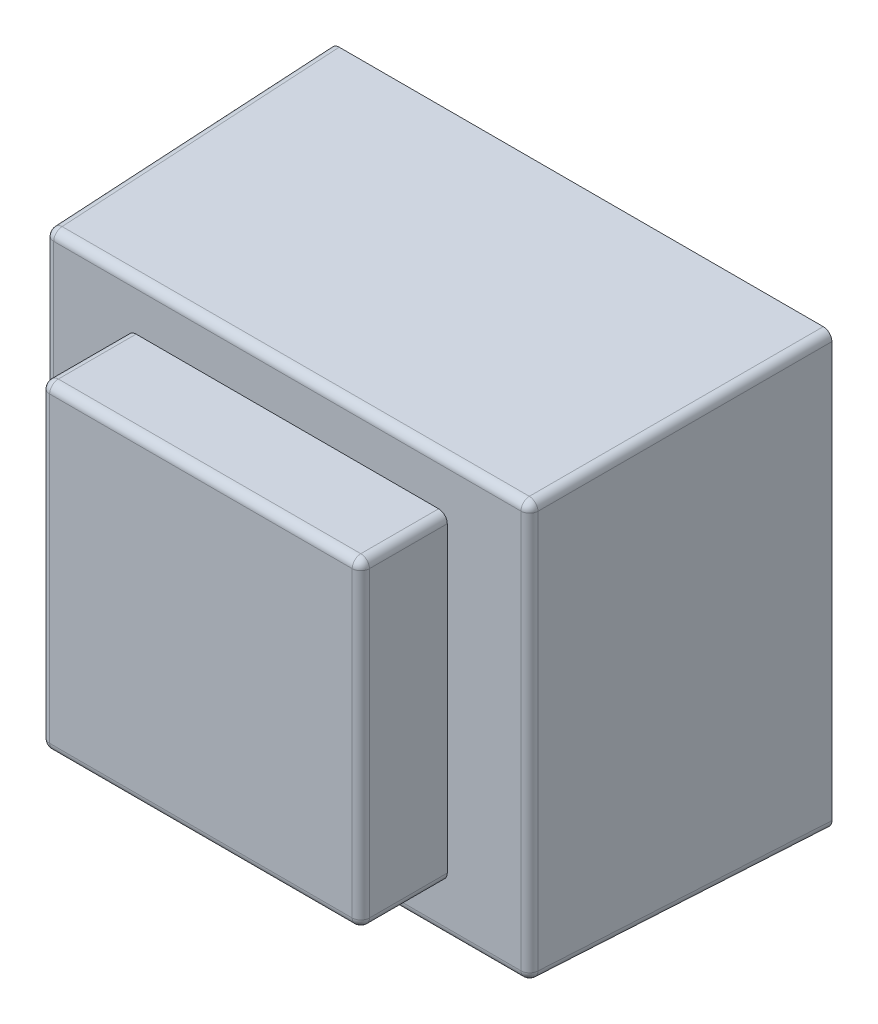
SolidWorks part; units mm, degrees
material "Медь"
ref_plane "Спереди (Плоскость XY)" through (0, 0, 0) normal (0, 0, 1) x (1, 0, 0)
ref_plane "Сверху (Плоскость XZ)" through (0, 0, 0) normal (0, 1, 0) x (1, 0, 0)
ref_plane "Справа (Плоскость ZY)" through (0, 0, 0) normal (1, 0, 0) x (0, 0, -1)
sketch "Эскиз1" plane through (0, 0, 0) normal (0, 1, 0) x (1, 0, 0)
  line L0 (0, 0) -> (58, 0) construction
  line L1 (-29, 0) -> (-28, -34)
  line L2 (-28, -34) -> (28, -34)
  line L3 (28, -34) -> (29, 0)
  line L4 (29, 0) -> (-29, 0)
  line L5 (0, 0) -> (0, -34) construction
  point P9 (0, 0)
  point P12 (81.2325, -36.5426)
  dimension "D1" = 58
  dimension "D2" = 56
  dimension "D3" = 34
  dimension "D4" = 58
extrude "Бобышка-Вытянуть3" add sketch "Эскиз1" along normal mid plane 50
sketch "Эскиз3" plane through (0, 0, 0) normal (1, 0, 0) x (0, 0, -1)
  line L2 (-34, 25) -> (-34, -25) construction
  line L3 (0, 25) -> (-34, 24)
  line L4 (0, -25) -> (-34, -24)
  line L8 (0, -25) -> (0, 25)
  line L10 (-34, 24) -> (-34, -24)
  line L11 (-34, 0) -> (0, 0) construction
  dimension "D1" = 48
extrude "Вырез-Вытянуть1" cut sketch "Эскиз3" along normal through all both and the other way through all flip side to cut
sketch "Эскиз4" plane through (0, 0, 34) normal (0, 0, 1) x (1, 0, 0)
  line L1 (-18.5, -18.5) -> (18.5, -18.5)
  line L2 (-18.5, -18.5) -> (-18.5, 18.5)
  line L3 (-18.5, 18.5) -> (18.5, 18.5)
  line L4 (18.5, -18.5) -> (18.5, 18.5)
  line L5 (-18.5, -18.5) -> (18.5, 18.5) construction
  line L6 (-18.5, 18.5) -> (18.5, -18.5) construction
  point P0 (0, 0)
  point P5 (0, 0)
  dimension "D1" = 37
extrude "Бобышка-Вытянуть4" add sketch "Эскиз4" along normal blind 10
sketch "Эскиз8" plane through (0, 0, 0) normal (0, 0, -1) x (1, 0, 0)
  line L0 (-22, 0) -> (22, 0) construction
  line L1 (20.6, 1.4) -> (23.4, 1.4)
  line L2 (20.6, 1.4) -> (20.6, -1.4)
  line L3 (20.6, -1.4) -> (23.4, -1.4)
  line L4 (23.4, 1.4) -> (23.4, -1.4)
  line L5 (20.6, 1.4) -> (23.4, -1.4) construction
  line L6 (20.6, -1.4) -> (23.4, 1.4) construction
  line L7 (-23.4, 1.4) -> (-20.6, 1.4)
  line L8 (-23.4, 1.4) -> (-23.4, -1.4)
  line L9 (-23.4, -1.4) -> (-20.6, -1.4)
  line L10 (-20.6, 1.4) -> (-20.6, -1.4)
  line L11 (-23.4, 1.4) -> (-20.6, -1.4) construction
  line L12 (-23.4, -1.4) -> (-20.6, 1.4) construction
  point P0 (22, 0)
  point P5 (-22, 0)
  point P12 (0, 0)
  point P13 (0, 0)
  dimension "D1" = 2.8
  dimension "D2" = 44
extrude "Вырез-Вытянуть3" cut sketch "Эскиз8" against normal blind 10
sketch "Эскиз5" plane through (0, 0, 0) normal (0, 0, -1) x (1, 0, 0)
  line L4 (27.5, 23.5) -> (-27.5, 23.5)
  line L5 (27.5, 23.5) -> (-27.5, 23.5)
  line L6 (-27.5, -23.5) -> (27.5, -23.5)
  line L12 (-27.5, -23.5) -> (27.5, -23.5)
  line L13 (27.5, -23.5) -> (27.5, 23.5)
  line L15 (-27.5, 23.5) -> (-27.5, -23.5)
  line L17 (27.5, -23.5) -> (27.5, 23.5)
  line L19 (-27.5, 23.5) -> (-27.5, -23.5)
  dimension "D1" = 1.5
extrude "Вырез-Вытянуть2" cut sketch "Эскиз5" against normal blind 0.7
fillet "Скругление1" radius 1 16 edges at (0, -18.5, 44) (-18.5, 0, 44) (0, 18.5, 44) (18.5, 0, 44) (-18.5, 18.5, 39) (-18.5, -18.5, 39) (18.5, -18.5, 39) (18.5, 18.5, 39) (28, 0, 34) (-28, 0, 34) (-28.5, 24.5, 17) (-28.5, -24.5, 17) (0, -24, 34) (28.5, -24.5, 17) (28.5, 24.5, 17) (0, 24, 34)
sketch "Эскиз7" plane through (0, -0.7, 0.7) normal (0, 0, -1) x (1, 0, 0)
  line L0 (0, 0) -> (56.4992, 0) construction
  line L1 (5, 15.8) -> (-5, 15.8) construction
  line L3 (0, -17.2) -> (0, 15.8) construction
  circle A0 centre (0, 15.8) radius 0.4 construction
  circle A1 centre (-15, 15.8) radius 0.4
  circle A2 centre (-5, 15.8) radius 0.4 construction
  circle A3 centre (5, 15.8) radius 0.4 construction
  circle A4 centre (15, 15.8) radius 0.4
  circle A5 centre (-15, -17.2) radius 0.4 construction
  circle A6 centre (-10, -17.2) radius 0.4
  circle A7 centre (-5, -17.2) radius 0.4 construction
  circle A8 centre (0, -17.2) radius 0.4 construction
  circle A9 centre (5, -17.2) radius 0.4 construction
  circle A10 centre (10, -17.2) radius 0.4
  circle A11 centre (15, -17.2) radius 0.4 construction
  point P11 (0, 0)
  point P18 (15.5258, -18.8904)
  point P28 (0, 0)
  point P29 (0, 0)
  dimension "D2" = 0.8
  dimension "D1" = 5
  dimension "D3" = 10
  dimension "D4" = 33
  dimension "D5" = 7
extrude "Бобышка-Вытянуть5" add sketch "Эскиз7" along normal blind 4 from surface at 0.7 separate body starting at face at (0, 0, 0)
